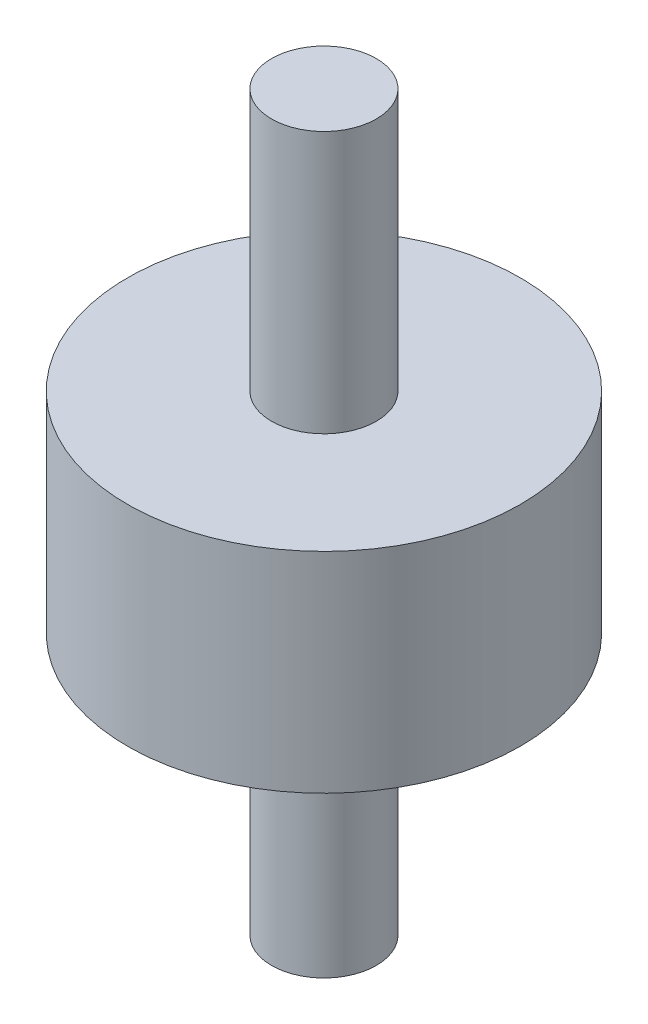
SolidWorks part; units mm, degrees
ref_plane "Front Plane" through (0, 0, 0) normal (0, 0, 1) x (1, 0, 0)
ref_plane "Top Plane" through (0, 0, 0) normal (0, 1, 0) x (1, 0, 0)
ref_plane "Right Plane" through (0, 0, 0) normal (1, 0, 0) x (0, 0, -1)
sketch "Sketch1" plane through (0, 0, 0) normal (0, 0, 1) x (1, 0, 0)
  line L0 (0, 28) -> (-2, 28)
  line L1 (-2, 28) -> (-2, 18)
  line L2 (-2, 18) -> (-7.5, 18)
  line L3 (-7.5, 18) -> (-7.5, 10)
  line L4 (-7.5, 10) -> (-2, 10)
  line L5 (-2, 10) -> (-2, 0)
  line L6 (-2, 0) -> (0, 0)
  line L7 (0, 0) -> (0, 28)
  dimension "D1" = 2
  dimension "D2" = 10
  dimension "D3" = 10
  dimension "D4" = 8
  dimension "D5" = 7.5
revolve "Revolve1" add sketch "Sketch1" angle 360 about L7
